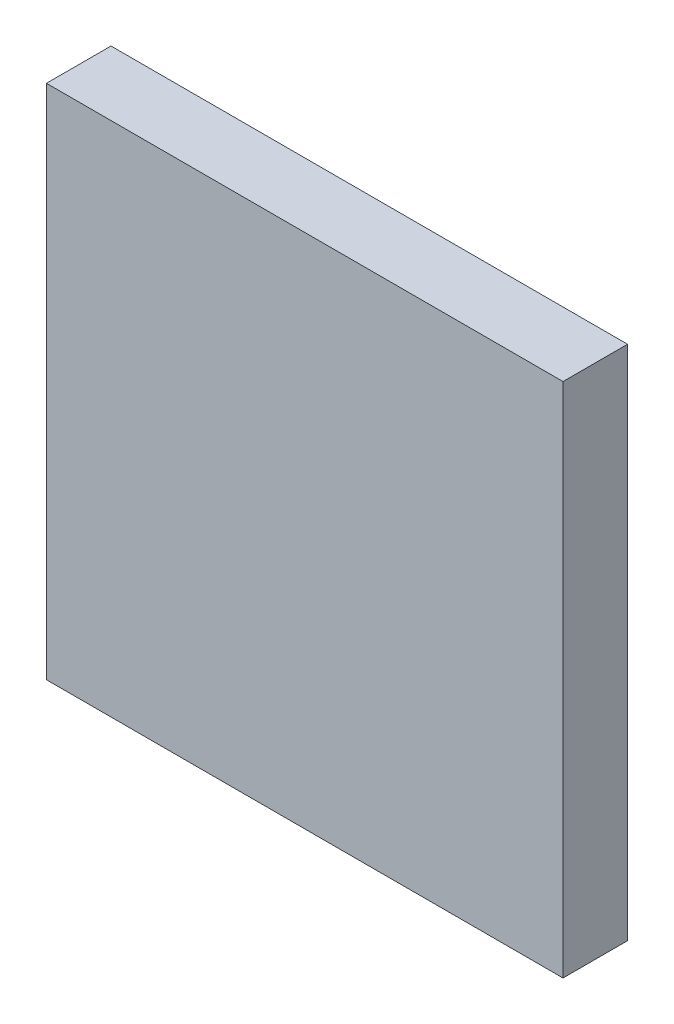
SolidWorks part; units mm, degrees
ref_plane "Front Plane" through (0, 0, 0) normal (0, 0, 1) x (1, 0, 0)
ref_plane "Top Plane" through (0, 0, 0) normal (0, 1, 0) x (1, 0, 0)
ref_plane "Right Plane" through (0, 0, 0) normal (1, 0, 0) x (0, 0, -1)
sketch "Sketch1" plane through (0, 0, 0) normal (0, 0, 1) x (1, 0, 0)
  line L1 (0, 0) -> (25.4, 0)
  line L2 (0, 0) -> (0, 25.4)
  line L3 (0, 25.4) -> (25.4, 25.4)
  line L4 (25.4, 0) -> (25.4, 25.4)
  dimension "D1" = 25.4
  dimension "D2" = 25.4
extrude "Boss-Extrude1" add sketch "Sketch1" along normal blind 3.175
